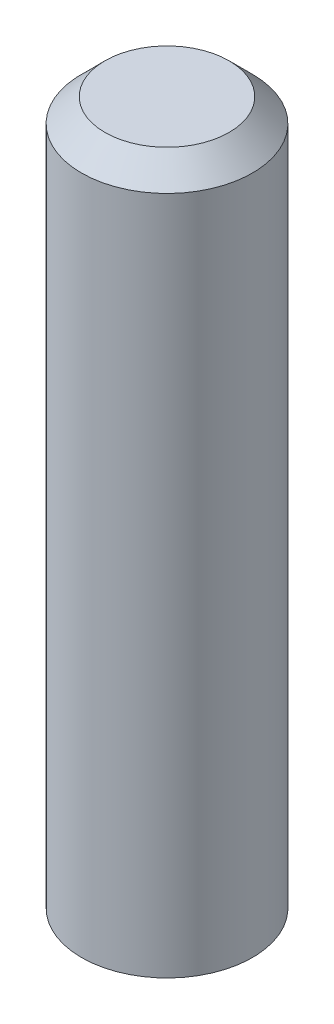
SolidWorks part; units mm, degrees
ref_plane "Front Plane" through (0, 0, 0) normal (0, 0, 1) x (1, 0, 0)
ref_plane "Top Plane" through (0, 0, 0) normal (0, 1, 0) x (1, 0, 0)
ref_plane "Right Plane" through (0, 0, 0) normal (1, 0, 0) x (0, 0, -1)
sketch "Sketch1" plane through (0, 0, 0) normal (0, 1, 0) x (1, 0, 0)
  circle A0 centre (0, 0) radius 9.271
  dimension "D1" = 18.542
extrude "Boss-Extrude1" add sketch "Sketch1" along normal blind 76.2
chamfer "Chamfer2" distance 2.54 angle 45 1 edges at (0, 76.2, 9.271)
